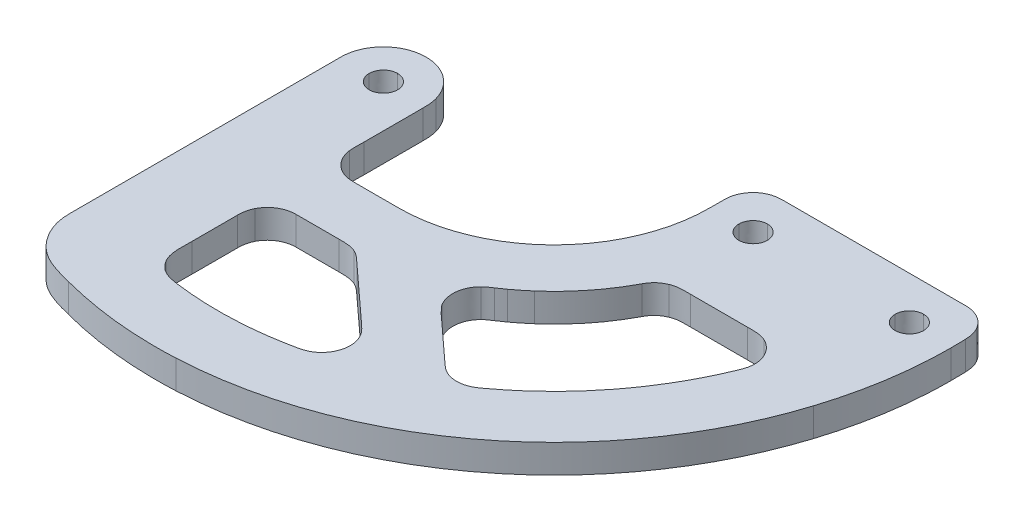
SolidWorks part; units mm, degrees
ref_plane "Front Plane" through (0, 0, 0) normal (0, 0, 1) x (1, 0, 0)
ref_plane "Top Plane" through (0, 0, 0) normal (0, 1, 0) x (1, 0, 0)
ref_plane "Right Plane" through (0, 0, 0) normal (1, 0, 0) x (0, 0, -1)
sketch "Imported Profile" plane through (0, 0, 0) normal (0, 1, 0) x (1, 0, 0)
  spline S0 degree 3 poles (0.2386, 77.0121) (0.1972, 76.9636) (0.2385, 77.0756) (0.2385, 77.1101) knots 0 0 0 0 1 1 1 1
  spline S1 degree 3 poles (0.2385, 77.1101) (0.2385, 77.1451) (0.2385, 77.1721) (0.2385, 77.2066) knots 0 0 0 0 1 1 1 1
  spline S2 degree 3 poles (0.2385, 77.2066) (0.2385, 77.2686) (0.2385, 77.3376) (0.2455, 77.3996) knots 0 0 0 0 1 1 1 1
  spline S3 degree 3 poles (0.2455, 77.3996) (0.2455, 77.5306) (0.2596, 77.6616) (0.2661, 77.7926) knots 0 0 0 0 1 1 1 1
  spline S4 degree 3 poles (0.2661, 77.7926) (0.2936, 78.0611) (0.3212, 78.3231) (0.3695, 78.585) knots 0 0 0 0 1 1 1 1
  spline S5 degree 3 poles (0.3695, 78.585) (0.4591, 79.1362) (0.5969, 79.6736) (0.7829, 80.1973) knots 0 0 0 0 1 1 1 1
  spline S6 degree 3 poles (0.7829, 80.1973) (1.1895, 81.3342) (1.7475, 82.3057) (2.533, 83.2152) knots 0 0 0 0 1 1 1 1
  spline S7 degree 3 poles (2.533, 83.2152) (4.0558, 84.9928) (6.1779, 86.1435) (8.493, 86.4535) knots 0 0 0 0 1 1 1 1
  spline S8 degree 3 poles (8.493, 86.4535) (13.2059, 87.0875) (17.6501, 84.166) (18.9317, 79.584) knots 0 0 0 0 1 1 1 1
  spline S9 degree 3 poles (18.9317, 79.584) (19.228, 78.5298) (19.29, 77.4756) (19.29, 76.387) knots 0 0 0 0 1 1 1 1
  spline S10 degree 3 poles (19.29, 76.387) (19.29, 75.2846) (19.29, 74.1821) (19.29, 73.0797) knots 0 0 0 0 1 1 1 1
  spline S11 degree 3 poles (19.29, 73.0797) (19.29, 70.8748) (19.29, 68.6631) (19.29, 66.4582) knots 0 0 0 0 1 1 1 1
  spline S12 degree 3 poles (19.29, 66.4582) (19.29, 65.3558) (19.29, 64.2534) (19.29, 63.151) knots 0 0 0 0 1 1 1 1
  spline S13 degree 3 poles (19.29, 63.151) (19.29, 62.0623) (19.2004, 60.9736) (19.3313, 59.885) knots 0 0 0 0 1 1 1 1
  spline S14 degree 3 poles (19.3313, 59.885) (19.6, 57.5217) (21.171, 55.5097) (23.3965, 54.6691) knots 0 0 0 0 1 1 1 1
  spline S15 degree 3 poles (23.3965, 54.6691) (24.4576, 54.2696) (25.498, 54.2626) (26.5935, 54.2626) knots 0 0 0 0 1 1 1 1
  spline S16 degree 3 poles (26.5935, 54.2626) (27.6891, 54.2626) (28.7847, 54.2626) (29.8802, 54.2626) knots 0 0 0 0 1 1 1 1
  spline S17 degree 3 poles (29.8802, 54.2626) (32.0506, 54.2626) (34.221, 54.2276) (36.3914, 54.2676) knots 0 0 0 0 1 1 1 1
  spline S18 degree 3 poles (36.3914, 54.2676) (40.8494, 54.3501) (44.9352, 55.1978) (49.0556, 56.8927) knots 0 0 0 0 1 1 1 1
  spline S19 degree 3 poles (49.0556, 56.8927) (57.8199, 60.5033) (64.7377, 67.5174) (68.231, 76.3369) knots 0 0 0 0 1 1 1 1
  spline S20 degree 3 poles (68.231, 76.3369) (69.9053, 80.5743) (70.677, 84.7567) (70.677, 89.318) knots 0 0 0 0 1 1 1 1
  spline S21 degree 3 poles (70.677, 89.318) (70.677, 90.4342) (70.6355, 91.5504) (70.691, 92.6666) knots 0 0 0 0 1 1 1 1
  spline S22 degree 3 poles (70.691, 92.6666) (70.7461, 93.8793) (71.0768, 94.8784) (71.7521, 95.8843) knots 0 0 0 0 1 1 1 1
  spline S23 degree 3 poles (71.7521, 95.8843) (72.4618, 96.9524) (73.3093, 97.662) (74.4875, 98.1788) knots 0 0 0 0 1 1 1 1
  spline S24 degree 3 poles (74.4875, 98.1788) (75.5624, 98.6473) (76.6234, 98.7093) (77.7603, 98.7093) knots 0 0 0 0 1 1 1 1
  spline S25 degree 3 poles (77.7603, 98.7093) (86.752, 98.7093) (95.7506, 98.7093) (104.7423, 98.7093) knots 0 0 0 0 1 1 1 1
  spline S26 degree 3 poles (104.7423, 98.7093) (109.2141, 98.7093) (113.6858, 98.7093) (118.1575, 98.7093) knots 0 0 0 0 1 1 1 1
  spline S27 degree 3 poles (118.1575, 98.7093) (120.5691, 98.7093) (122.7119, 97.5449) (123.8764, 95.402) knots 0 0 0 0 1 1 1 1
  spline S28 degree 3 poles (123.8764, 95.402) (124.4414, 94.3685) (124.6205, 93.3419) (124.6619, 92.1981) knots 0 0 0 0 1 1 1 1
  spline S29 degree 3 poles (124.6619, 92.1981) (124.6964, 91.1025) (124.7169, 90.0139) (124.7099, 88.9183) knots 0 0 0 0 1 1 1 1
  spline S30 degree 3 poles (124.7099, 88.9183) (124.6894, 79.7475) (123.3318, 71.0865) (120.5689, 62.3429) knots 0 0 0 0 1 1 1 1
  spline S31 degree 3 poles (120.5689, 62.3429) (109.3447, 26.8722) (77.2296, 2.1364) (40.0776, 0.3311) knots 0 0 0 0 1 1 1 1
  spline S32 degree 3 poles (40.0776, 0.3311) (30.9137, -0.1169) (22.1907, 0.7927) (13.3162, 3.101) knots 0 0 0 0 1 1 1 1
  spline S33 degree 3 poles (13.3162, 3.101) (8.7686, 4.2861) (4.855, 5.2783) (2.092, 9.8121) knots 0 0 0 0 1 1 1 1
  spline S34 degree 3 poles (2.092, 9.8121) (0.8449, 11.8515) (0.2661, 13.8635) (0.2386, 16.2613) knots 0 0 0 0 1 1 1 1
  spline S35 degree 3 poles (0.2386, 16.2613) (0.2111, 18.4869) (0.2386, 20.7192) (0.2386, 22.9516) knots 0 0 0 0 1 1 1 1
  spline S36 degree 3 poles (0.2386, 22.9516) (0.2386, 40.9695) (0.2386, 58.9942) (0.2386, 77.0121) knots 0 0 0 0 1 1 1 1
  spline S37 degree 3 poles (77.7944, 66.8094) (75.0315, 61.614) (71.6002, 57.287) (67.1766, 53.4009) knots 0 0 0 0 1 1 1 1
  spline S38 degree 3 poles (67.1766, 53.4009) (66.1087, 52.457) (64.9925, 51.5681) (63.8349, 50.7207) knots 0 0 0 0 1 1 1 1
  spline S39 degree 3 poles (63.8349, 50.7207) (63.263, 50.3002) (62.6773, 49.8939) (62.0848, 49.5011) knots 0 0 0 0 1 1 1 1
  spline S40 degree 3 poles (62.0848, 49.5011) (61.4922, 49.1081) (60.8928, 48.7432) (60.3898, 48.2333) knots 0 0 0 0 1 1 1 1
  spline S41 degree 3 poles (60.3898, 48.2333) (58.2539, 46.1042) (57.9093, 42.7762) (59.563, 40.2613) knots 0 0 0 0 1 1 1 1
  spline S42 degree 3 poles (59.563, 40.2613) (60.1486, 39.3656) (61.8298, 37.9118) (62.5878, 37.2227) knots 0 0 0 0 1 1 1 1
  spline S43 degree 3 poles (62.5878, 37.2227) (63.6489, 36.2512) (64.71, 35.2797) (65.7642, 34.3082) knots 0 0 0 0 1 1 1 1
  spline S44 degree 3 poles (65.7642, 34.3082) (66.8252, 33.3436) (67.8863, 32.3721) (68.9405, 31.4005) knots 0 0 0 0 1 1 1 1
  spline S45 degree 3 poles (68.9405, 31.4005) (69.4711, 30.918) (70.0016, 30.429) (70.5322, 29.9468) knots 0 0 0 0 1 1 1 1
  spline S46 degree 3 poles (70.5322, 29.9468) (71.0489, 29.4643) (71.5519, 28.9614) (72.11, 28.5273) knots 0 0 0 0 1 1 1 1
  spline S47 degree 3 poles (72.11, 28.5273) (73.3847, 27.5421) (74.618, 27.1493) (76.2235, 27.2044) knots 0 0 0 0 1 1 1 1
  spline S48 degree 3 poles (76.2235, 27.2044) (77.7806, 27.2664) (78.952, 27.8452) (80.1647, 28.7409) knots 0 0 0 0 1 1 1 1
  spline S49 degree 3 poles (80.1647, 28.7409) (82.4522, 30.4221) (84.6295, 32.2136) (86.7172, 34.1497) knots 0 0 0 0 1 1 1 1
  spline S50 degree 3 poles (86.7172, 34.1497) (90.9685, 38.084) (94.6478, 42.3697) (97.8931, 47.1722) knots 0 0 0 0 1 1 1 1
  spline S51 degree 3 poles (97.8931, 47.1722) (99.5123, 49.57) (100.9799, 52.0366) (102.3166, 54.5998) knots 0 0 0 0 1 1 1 1
  spline S52 degree 3 poles (102.3166, 54.5998) (103.0539, 56.0261) (105.3827, 60.801) (105.7479, 62.4202) knots 0 0 0 0 1 1 1 1
  spline S53 degree 3 poles (105.7479, 62.4202) (106.4163, 65.3485) (104.9418, 68.3389) (102.2201, 69.5929) knots 0 0 0 0 1 1 1 1
  spline S54 degree 3 poles (102.2201, 69.5929) (100.8283, 70.2336) (99.4572, 70.1785) (98.0172, 70.1785) knots 0 0 0 0 1 1 1 1
  spline S55 degree 3 poles (98.0172, 70.1785) (96.5977, 70.1785) (95.1715, 70.1785) (93.7521, 70.1785) knots 0 0 0 0 1 1 1 1
  spline S56 degree 3 poles (93.7521, 70.1785) (90.8927, 70.1785) (88.0401, 70.1785) (85.1876, 70.1785) knots 0 0 0 0 1 1 1 1
  spline S57 degree 3 poles (85.1876, 70.1785) (83.7476, 70.1785) (82.3626, 70.275) (80.957, 69.6895) knots 0 0 0 0 1 1 1 1
  spline S58 degree 3 poles (80.957, 69.6895) (79.4963, 69.0763) (78.5386, 68.2081) (77.7944, 66.8094) knots 0 0 0 0 1 1 1 1
  spline S59 degree 3 poles (25.6357, 41.5636) (27.7923, 41.5636) (29.949, 41.5636) (32.0987, 41.5636) knots 0 0 0 0 1 1 1 1
  spline S60 degree 3 poles (32.0987, 41.5636) (33.1735, 41.5636) (34.2553, 41.5636) (35.3302, 41.5636) knots 0 0 0 0 1 1 1 1
  spline S61 degree 3 poles (35.3302, 41.5636) (36.6669, 41.5636) (37.9347, 41.5786) (39.2231, 40.9917) knots 0 0 0 0 1 1 1 1
  spline S62 degree 3 poles (39.2231, 40.9917) (40.298, 40.4957) (41.0835, 39.7032) (41.9241, 38.9246) knots 0 0 0 0 1 1 1 1
  spline S63 degree 3 poles (41.9241, 38.9246) (42.7647, 38.1598) (43.6053, 37.3881) (44.4459, 36.6164) knots 0 0 0 0 1 1 1 1
  spline S64 degree 3 poles (44.4459, 36.6164) (46.1271, 35.0799) (47.8083, 33.5434) (49.4895, 32) knots 0 0 0 0 1 1 1 1
  spline S65 degree 3 poles (49.4895, 32) (51.1501, 30.4773) (52.8175, 28.9476) (54.4849, 27.4249) knots 0 0 0 0 1 1 1 1
  spline S66 degree 3 poles (54.4849, 27.4249) (55.3324, 26.6463) (56.1041, 25.8746) (56.5864, 24.786) knots 0 0 0 0 1 1 1 1
  spline S67 degree 3 poles (56.5864, 24.786) (57.0894, 23.6629) (57.241, 22.6018) (57.0894, 21.3822) knots 0 0 0 0 1 1 1 1
  spline S68 degree 3 poles (57.0894, 21.3822) (56.7862, 19.0464) (55.2153, 17.069) (53.0104, 16.249) knots 0 0 0 0 1 1 1 1
  spline S69 degree 3 poles (53.0104, 16.249) (51.7909, 15.7875) (47.6223, 15.1121) (46.3614, 14.933) knots 0 0 0 0 1 1 1 1
  spline S70 degree 3 poles (46.3614, 14.933) (41.8207, 14.2853) (37.3146, 14.0579) (32.7395, 14.2371) knots 0 0 0 0 1 1 1 1
  spline S71 degree 3 poles (32.7395, 14.2371) (30.4795, 14.3266) (28.2402, 14.5196) (26.0009, 14.8158) knots 0 0 0 0 1 1 1 1
  spline S72 degree 3 poles (26.0009, 14.8158) (23.5204, 15.1398) (21.6187, 15.6358) (20.1924, 18.006) knots 0 0 0 0 1 1 1 1
  spline S73 degree 3 poles (20.1924, 18.006) (18.9729, 20.0386) (19.2898, 22.6086) (19.2898, 24.6895) knots 0 0 0 0 1 1 1 1
  spline S74 degree 3 poles (19.2898, 24.6895) (19.2898, 26.9632) (19.2898, 29.2371) (19.2898, 31.5108) knots 0 0 0 0 1 1 1 1
  spline S75 degree 3 poles (19.2898, 31.5108) (19.2898, 32.627) (19.2898, 33.7432) (19.2898, 34.8664) knots 0 0 0 0 1 1 1 1
  spline S76 degree 3 poles (19.2898, 34.8664) (19.2898, 36.017) (19.4482, 37.0505) (19.9788, 38.1047) knots 0 0 0 0 1 1 1 1
  spline S77 degree 3 poles (19.9788, 38.1047) (21.0675, 40.2269) (23.2517, 41.5636) (25.6357, 41.5636) knots 0 0 0 0 1 1 1 1
  spline S78 degree 3 poles (83.3824, 89.1886) (83.3824, 90.9387) (81.9561, 92.365) (80.206, 92.365) knots 0 0 0 0 1 1 1 1
  spline S79 degree 3 poles (80.206, 92.365) (78.4559, 92.365) (77.0296, 90.9387) (77.0296, 89.1886) knots 0 0 0 0 1 1 1 1
  spline S80 degree 3 poles (77.0296, 89.1886) (77.0296, 87.4316) (78.4559, 86.0122) (80.206, 86.0122) knots 0 0 0 0 1 1 1 1
  spline S81 degree 3 poles (80.206, 86.0122) (81.9561, 86.0122) (83.3824, 87.4316) (83.3824, 89.1886) knots 0 0 0 0 1 1 1 1
  spline S82 degree 3 poles (12.9371, 77.0136) (12.9371, 78.7706) (11.5177, 80.19) (9.7607, 80.19) knots 0 0 0 0 1 1 1 1
  spline S83 degree 3 poles (9.7607, 80.19) (8.0106, 80.19) (6.5843, 78.7706) (6.5843, 77.0136) knots 0 0 0 0 1 1 1 1
  spline S84 degree 3 poles (6.5843, 77.0136) (6.5843, 75.2635) (8.0106, 73.8372) (9.7607, 73.8372) knots 0 0 0 0 1 1 1 1
  spline S85 degree 3 poles (9.7607, 73.8372) (11.5177, 73.8372) (12.9371, 75.2635) (12.9371, 77.0136) knots 0 0 0 0 1 1 1 1
  spline S86 degree 3 poles (118.3019, 89.1886) (118.3019, 90.9387) (116.8825, 92.365) (115.1324, 92.365) knots 0 0 0 0 1 1 1 1
  spline S87 degree 3 poles (115.1324, 92.365) (113.3754, 92.365) (111.956, 90.9387) (111.956, 89.1886) knots 0 0 0 0 1 1 1 1
  spline S88 degree 3 poles (111.956, 89.1886) (111.956, 87.4316) (113.3754, 86.0122) (115.1324, 86.0122) knots 0 0 0 0 1 1 1 1
  spline S89 degree 3 poles (115.1324, 86.0122) (116.8825, 86.0122) (118.3019, 87.4316) (118.3019, 89.1886) knots 0 0 0 0 1 1 1 1
extrude "Boss-Extrude1" add sketch "Imported Profile" along normal blind 6.35
